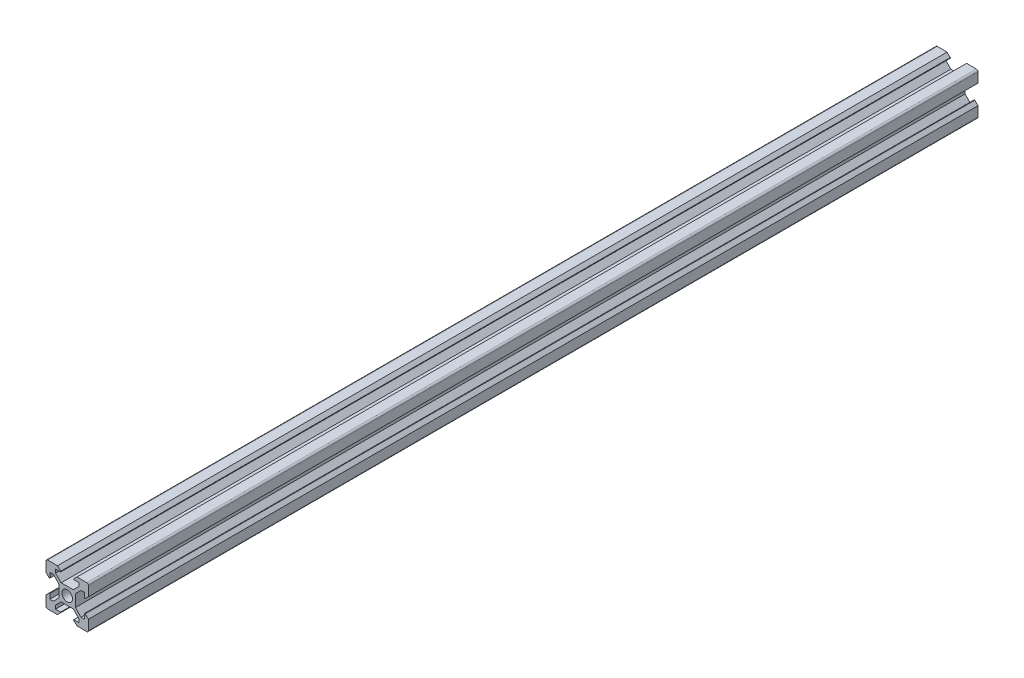
SolidWorks part; units mm, degrees
ref_plane "Alzado" through (0, 0, 0) normal (0, 0, 1) x (1, 0, 0)
ref_plane "Planta" through (0, 0, 0) normal (0, 1, 0) x (1, 0, 0)
ref_plane "Vista lateral" through (0, 0, 0) normal (1, 0, 0) x (0, 0, -1)
sketch "Croquis1" plane through (0, 0, 0) normal (0, 0, 1) x (1, 0, 0)
  line L0 (-4.6, 10) -> (-3.1, 8.5)
  line L3 (-4.6, 10) -> (-9.25, 10)
  line L5 (-3.1, 8.5) -> (-3.1, 8.2)
  line L6 (-3.1, 8.2) -> (-5.5, 8.2)
  line L7 (-5.5, 8.2) -> (-5.5, 6.5607)
  line L8 (-5.5, 6.5607) -> (-2.84, 3.9007)
  line L9 (-2.84, 3.9007) -> (0, 3.9007)
  line L10 (0, 0) -> (-15.3499, 15.3499) construction
  line L11 (-3.9007, 2.84) -> (-3.9007, 0)
  line L12 (-6.5607, 5.5) -> (-3.9007, 2.84)
  line L13 (-8.2, 5.5) -> (-6.5607, 5.5)
  line L14 (-8.2, 3.1) -> (-8.2, 5.5)
  line L15 (-8.5, 3.1) -> (-8.2, 3.1)
  line L16 (-10, 4.6) -> (-10, 9.25)
  line L17 (-10, 4.6) -> (-8.5, 3.1)
  line L18 (10, 4.6) -> (8.5, 3.1)
  line L19 (10, 4.6) -> (10, 9.25)
  line L20 (8.5, 3.1) -> (8.2, 3.1)
  line L21 (8.2, 3.1) -> (8.2, 5.5)
  line L22 (8.2, 5.5) -> (6.5607, 5.5)
  line L23 (6.5607, 5.5) -> (3.9007, 2.84)
  line L24 (3.9007, 2.84) -> (3.9007, 0)
  line L25 (5.5, 6.5607) -> (2.84, 3.9007)
  line L26 (5.5, 8.2) -> (5.5, 6.5607)
  line L27 (3.1, 8.2) -> (5.5, 8.2)
  line L28 (3.1, 8.5) -> (3.1, 8.2)
  line L29 (4.6, 10) -> (9.25, 10)
  line L30 (4.6, 10) -> (3.1, 8.5)
  line L31 (2.84, 3.9007) -> (0, 3.9007)
  line L32 (4.6, -10) -> (3.1, -8.5)
  line L33 (4.6, -10) -> (9.25, -10)
  line L34 (3.1, -8.5) -> (3.1, -8.2)
  line L35 (3.1, -8.2) -> (5.5, -8.2)
  line L36 (5.5, -8.2) -> (5.5, -6.5607)
  line L37 (5.5, -6.5607) -> (2.84, -3.9007)
  line L38 (2.84, -3.9007) -> (0, -3.9007)
  line L39 (6.5607, -5.5) -> (3.9007, -2.84)
  line L40 (8.2, -5.5) -> (6.5607, -5.5)
  line L41 (8.2, -3.1) -> (8.2, -5.5)
  line L42 (8.5, -3.1) -> (8.2, -3.1)
  line L43 (10, -4.6) -> (10, -9.25)
  line L44 (10, -4.6) -> (8.5, -3.1)
  line L45 (3.9007, -2.84) -> (3.9007, 0)
  line L46 (-10, -4.6) -> (-8.5, -3.1)
  line L47 (-10, -4.6) -> (-10, -9.25)
  line L48 (-8.5, -3.1) -> (-8.2, -3.1)
  line L49 (-8.2, -3.1) -> (-8.2, -5.5)
  line L50 (-8.2, -5.5) -> (-6.5607, -5.5)
  line L51 (-6.5607, -5.5) -> (-3.9007, -2.84)
  line L52 (-3.9007, -2.84) -> (-3.9007, 0)
  line L53 (-5.5, -6.5607) -> (-2.84, -3.9007)
  line L54 (-5.5, -8.2) -> (-5.5, -6.5607)
  line L55 (-3.1, -8.2) -> (-5.5, -8.2)
  line L56 (-3.1, -8.5) -> (-3.1, -8.2)
  line L57 (-4.6, -10) -> (-9.25, -10)
  line L58 (-4.6, -10) -> (-3.1, -8.5)
  line L59 (-2.84, -3.9007) -> (0, -3.9007)
  circle A0 centre (0, 0) radius 2.5
  arc A1 (-9.25, 10) -> (-10, 9.25) centre (-9.25, 9.25) ccw
  arc A2 (10, 9.25) -> (9.25, 10) centre (9.25, 9.25) ccw
  arc A3 (9.25, -10) -> (10, -9.25) centre (9.25, -9.25) ccw
  arc A4 (-10, -9.25) -> (-9.25, -10) centre (-9.25, -9.25) ccw
  point P18 (-10, 10)
  point P37 (10, 10)
  point P55 (10, -10)
  point P73 (-10, -10)
  point P79 (0, 0)
  dimension "D1" = 5
  dimension "D5" = 0.75
  dimension "D2" = 10
  dimension "D3" = 10
  dimension "D4" = 4.6
  dimension "D6" = 5.5
  dimension "D7" = 135
  dimension "D8" = 0.75
  dimension "D9" = 225
  dimension "D10" = 2.84
  dimension "D11" = 1.8
  dimension "D12" = 3.1
  dimension "D13" = 4
extrude "Saliente-Extruir1" add sketch "Croquis1" along normal blind 480
sketch "Sketch1" plane through (0, 0, 0) normal (1, 0, 0) x (0, 0, -1)
  line L0 (-60, 59.3377) -> (-60, -59.7305) construction
  line L1 (60, -12.1091) -> (-60, -12.1091)
  line L2 (60, -12.1091) -> (60, 12.1091)
  line L3 (60, 12.1091) -> (-60, 12.1091)
  line L4 (-60, -12.1091) -> (-60, 12.1091)
  line L5 (60, -12.1091) -> (-60, 12.1091) construction
  line L6 (60, 12.1091) -> (-60, -12.1091) construction
  line L7 (-480, -2.84) -> (-480, 2.84) construction
  point P0 (0, 0)
  dimension "D1" = 420
extrude "Cut-Extrude1" cut sketch "Sketch1" against normal blind 54 and the other way blind 46
